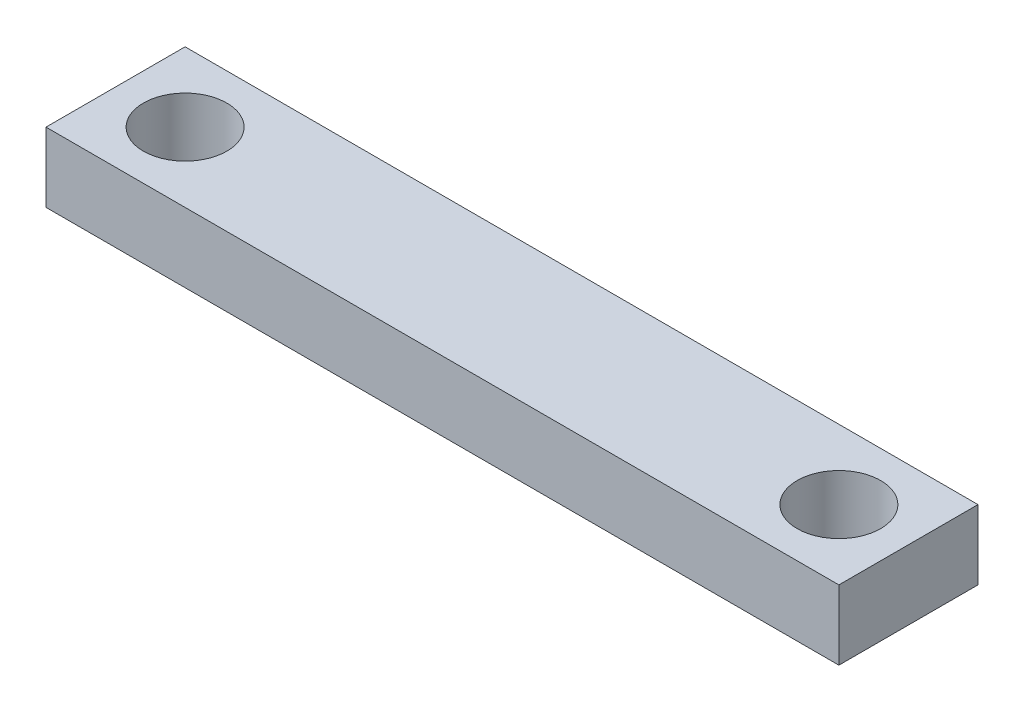
SolidWorks part; units mm, degrees
ref_plane "Front Plane" through (0, 0, 0) normal (0, 0, 1) x (1, 0, 0)
ref_plane "Top Plane" through (0, 0, 0) normal (0, 1, 0) x (1, 0, 0)
ref_plane "Right Plane" through (0, 0, 0) normal (1, 0, 0) x (0, 0, -1)
sketch "Sketch1" plane through (0, 0, 0) normal (0, 1, 0) x (1, 0, 0)
  line L1 (28.5, 5) -> (-28.5, 5)
  line L2 (28.5, 5) -> (28.5, -5)
  line L3 (28.5, -5) -> (-28.5, -5)
  line L4 (-28.5, 5) -> (-28.5, -5)
  line L5 (28.5, 5) -> (-28.5, -5) construction
  line L6 (28.5, -5) -> (-28.5, 5) construction
  circle A0 centre (-23.5, 0) radius 3
  circle A1 centre (23.5, 0) radius 3
  point P0 (0, 0)
  dimension "D3" = 6
  dimension "D1" = 10
  dimension "D2" = 57
  dimension "D4" = 5
  dimension "D5" = 5
  dimension "D6" = 47
extrude "Boss-Extrude1" add sketch "Sketch1" along normal mid plane 5
equation "\"D2@Sketch1\"= \"D6@Sketch1\" + 10mm"
